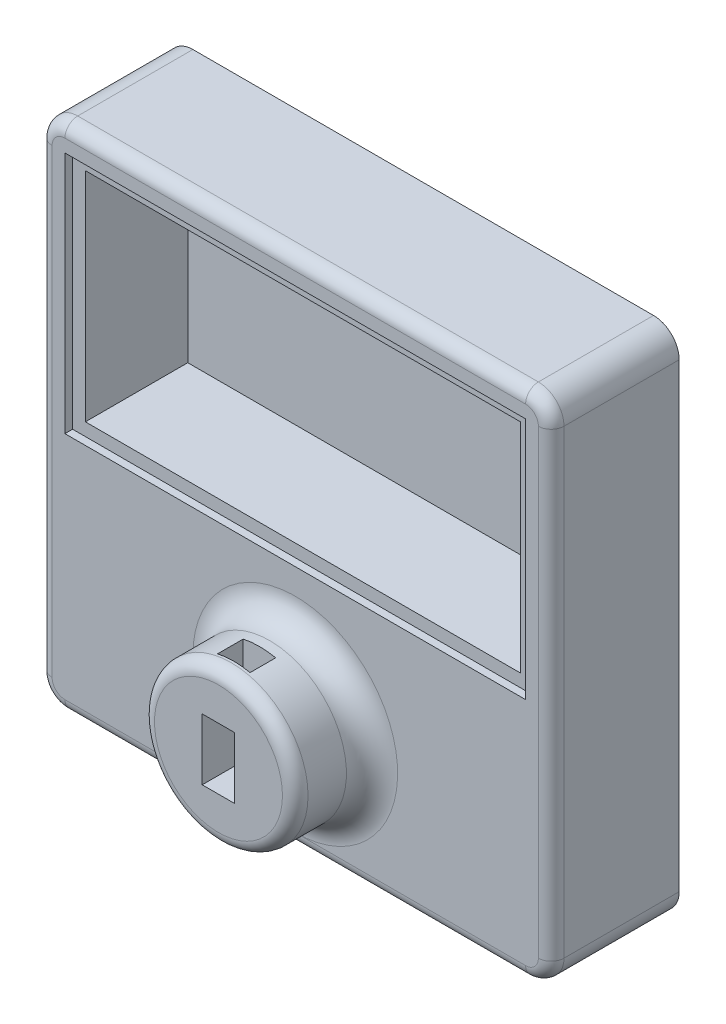
SolidWorks part; units mm, degrees
ref_plane "Přední rovina" through (0, 0, 0) normal (0, 0, 1) x (1, 0, 0)
ref_plane "Horní rovina" through (0, 0, 0) normal (0, 1, 0) x (1, 0, 0)
ref_plane "Pravá rovina" through (0, 0, 0) normal (1, 0, 0) x (0, 0, -1)
sketch "Skica1" plane through (0, 0, 0) normal (0, 0, 1) x (1, 0, 0)
  line L11 (0, 0) -> (200, 0)
  line L12 (0, 0) -> (0, 200)
  line L13 (0, 200) -> (200, 200)
  line L14 (200, 0) -> (200, 200)
  dimension "D1" = 200
  dimension "D2" = 200
extrude "Přidat vysunutím3" add sketch "Skica1" along normal blind 50
fillet "Zaoblit1" radius 10 4 edges at (200, 0, 25) (200, 200, 25) (0, 200, 25) (0, 0, 25)
sketch "Skica2" plane through (0, 0, 50) normal (0, 0, 1) x (1, 0, 0)
  line L0 (0, 190) -> (0, 10) construction
  line L1 (190, 200) -> (10, 200) construction
  circle A0 centre (100, 45) radius 30
  dimension "D1" = 60
  dimension "D2" = 100
  dimension "D3" = 155
extrude "Přidat vysunutím4" add sketch "Skica2" along normal blind 30
fillet "Zaoblit2" radius 10 1 edges at (70, 45, 50)
fillet "Zaoblit3" radius 5 1 edges at (130, 45, 80)
sketch "Skica4" plane through (0, 0, 50) normal (0, 0, 1) x (1, 0, 0)
  line L0 (0, 190) -> (0, 10) construction
  line L1 (10, 190) -> (190, 190)
  line L2 (10, 190) -> (10, 95)
  line L3 (10, 95) -> (190, 95)
  line L4 (190, 190) -> (190, 95)
  line L5 (190, 200) -> (10, 200) construction
  line L6 (200, 10) -> (200, 190) construction
  circle A0 centre (100, 45) radius 40 construction
  dimension "D1" = 10
  dimension "D2" = 10
  dimension "D3" = 10
  dimension "D4" = 50
extrude "Odebrat vysunutím1" cut sketch "Skica4" against normal blind 3
sketch "Skica7" plane through (0, 0, 47) normal (0, 0, 1) x (1, 0, 0)
  line L0 (190, 190) -> (10, 190) construction
  line L1 (15, 185) -> (185, 185)
  line L2 (15, 185) -> (15, 100)
  line L3 (15, 100) -> (185, 100)
  line L4 (185, 185) -> (185, 100)
  line L5 (10, 95) -> (190, 95) construction
  line L6 (190, 95) -> (190, 190) construction
  line L7 (10, 190) -> (10, 95) construction
  dimension "D1" = 5
  dimension "D2" = 5
  dimension "D3" = 5
  dimension "D4" = 5
extrude "Odebrat vysunutím2" cut sketch "Skica7" against normal blind 40
fillet "Zaoblit5" radius 5 8 edges at (2.9289, 2.9289, 50) (0, 100, 50) (2.9289, 197.0711, 50) (100, 200, 50) (197.0711, 197.0711, 50) (200, 100, 50) (197.0711, 2.9289, 50) (100, 0, 50)
sketch "Skica9" plane through (0, 0, 80) normal (0, 0, 1) x (1, 0, 0)
  line L0 (93.65, 57) -> (106.35, 33)
  line L1 (93.65, 57) -> (106.35, 57)
  line L2 (93.65, 57) -> (93.65, 33)
  line L3 (93.65, 33) -> (106.35, 33)
  line L4 (106.35, 57) -> (106.35, 33)
  line L5 (106.35, 57) -> (93.65, 33)
  line L6 (100, 70) -> (100, 20)
  line L7 (75, 45) -> (125, 45)
  circle A0 centre (100, 45) radius 25 construction
  point P9 (100, 45)
  point P12 (100, 45)
  dimension "D1" = 24
  dimension "D2" = 12.7
extrude "Odebrat vysunutím3" cut sketch "Skica9" against normal blind 16 contours L2 L7 L0 | L6 L1 L0 | L1 L6 L5 | L5 L7 L4 | L7 L0 L4 | L0 L6 L3 | L6 L5 L3 | L7 L2 L5
sketch "Skica10" plane through (0, 57, 0) normal (0, -1, 0) x (-1, 0, 0)
  line L0 (-93.65, -64) -> (-106.35, -64) construction
  line L1 (-93.65, -64) -> (-106.35, -64)
  line L2 (-93.65, -64) -> (-93.65, -74)
  line L3 (-93.65, -74) -> (-106.35, -74)
  line L4 (-106.35, -64) -> (-106.35, -74)
  line L5 (-106.35, -64) -> (-106.35, -80) construction
  dimension "D1" = 10
  dimension "D2" = 12.7
  dimension "D3" = 0
extrude "Odebrat vysunutím4" cut sketch "Skica10" against normal through all
